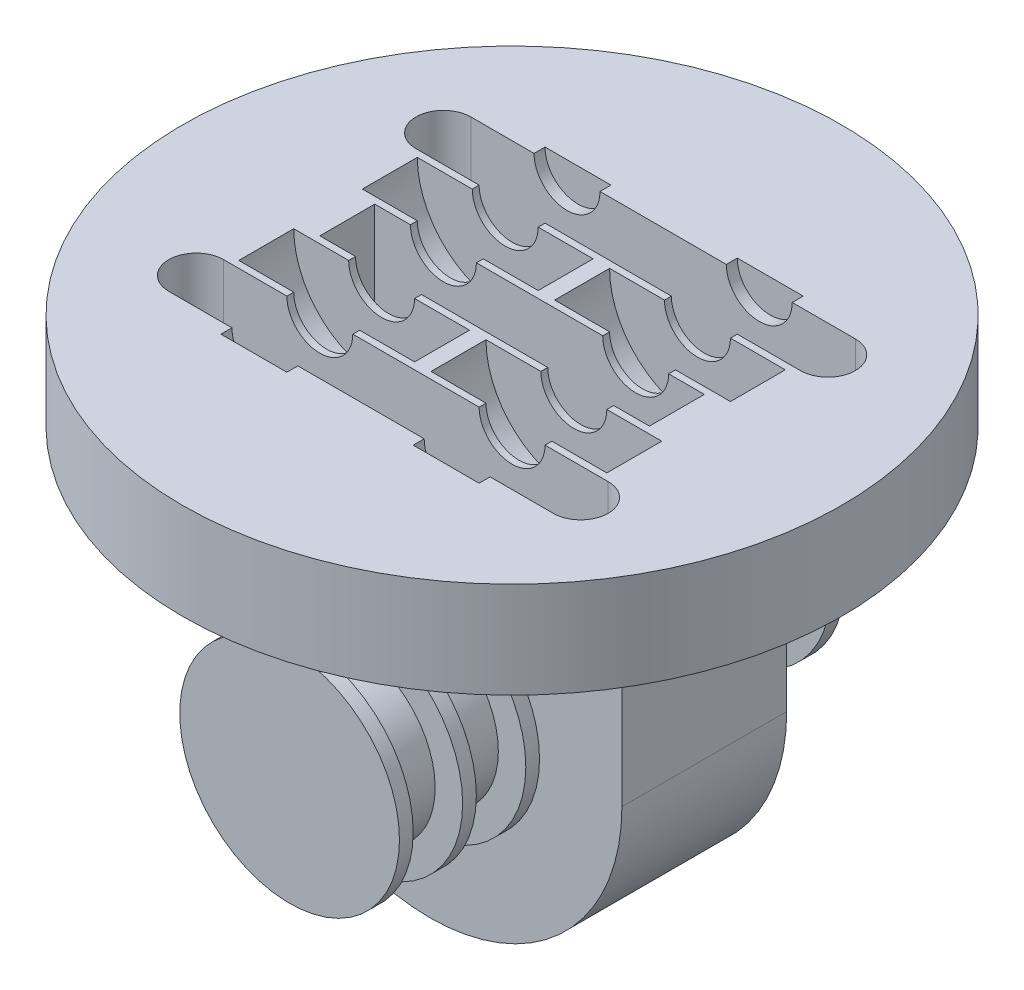
SolidWorks part; units mm, degrees
ref_plane "Front Plane" through (0, 0, 0) normal (0, 0, 1) x (1, 0, 0)
ref_plane "Top Plane" through (0, 0, 0) normal (0, 1, 0) x (1, 0, 0)
ref_plane "Right Plane" through (0, 0, 0) normal (1, 0, 0) x (0, 0, -1)
sketch "Sketch2" plane through (0, 0, 0) normal (0, 1, 0) x (1, 0, 0)
  circle A0 centre (0, 0) radius 60
  dimension "D1" = 120
extrude "Boss-Extrude1" add sketch "Sketch2" along normal blind 35
sketch "Sketch4" plane through (0, 0, 0) normal (0, 0, 1) x (1, 0, 0)
  line L0 (-35, 0) -> (-35, -35)
  line L1 (-60, 0) -> (60, 0) construction
  line L2 (0, 79.3854) -> (0, -134.1643) construction
  line L3 (35, 0) -> (35, -35)
  line L4 (-35, 0) -> (35, 0)
  arc A0 (-35, -35) -> (35, -35) centre (0, -35) ccw
  dimension "D1" = 35
  dimension "D2" = 35
extrude "Boss-Extrude2" add sketch "Sketch4" along normal mid plane 30
sketch "Sketch5" plane through (0, 0, 15) normal (0, 0, 1) x (1, 0, 0)
  line L0 (0, 0) -> (0, -35) construction
  line L1 (35, 0) -> (-35, 0) construction
  circle A0 centre (0, -35) radius 20
  dimension "D2" = 40
  dimension "D1" = 35
extrude "Boss-Extrude3" add sketch "Sketch5" along normal mid plane 5
sketch "Sketch6" plane through (0, 0, 17.5) normal (0, 0, 1) x (1, 0, 0)
  line L0 (0, 0) -> (0, -35) construction
  line L1 (35, 0) -> (-35, 0) construction
  circle A0 centre (0, -35) radius 15
  dimension "D2" = 30
  dimension "D1" = 35
extrude "Boss-Extrude4" add sketch "Sketch6" along normal blind 9
sketch "Sketch7" plane through (0, 0, 26.5) normal (0, 0, 1) x (1, 0, 0)
  line L0 (0, 0) -> (0, -35) construction
  line L1 (35, 0) -> (-35, 0) construction
  circle A0 centre (0, -35) radius 20
  dimension "D1" = 35
extrude "Boss-Extrude5" add sketch "Sketch7" along normal blind 2.5
sketch "Sketch8" plane through (0, 0, 29) normal (0, 0, 1) x (1, 0, 0)
  line L0 (0, 0) -> (0, -35) construction
  circle A0 centre (0, -35) radius 15
  dimension "D2" = 30
  dimension "D1" = 35
extrude "Boss-Extrude6" add sketch "Sketch8" along normal blind 9
sketch "Sketch9" plane through (0, 0, 38) normal (0, 0, 1) x (1, 0, 0)
  line L0 (0, 0) -> (0, -35) construction
  circle A0 centre (0, -35) radius 20
  dimension "D1" = 35
extrude "Boss-Extrude7" add sketch "Sketch9" along normal blind 2.5
mirror "Mirror1" about plane through (0, 0, 0) normal (0, 0, 1) of "Boss-Extrude3", "Boss-Extrude5", "Boss-Extrude4", "Boss-Extrude6", "Boss-Extrude7"
sketch "Sketch10" plane through (0, 35, 0) normal (0, 1, 0) x (1, 0, 0)
  line L0 (-56.8774, 0) -> (61.3412, 0) construction
  line L1 (-35, -22.5) -> (35, -22.5) construction
  line L2 (-35, -17.5) -> (35, -17.5)
  line L3 (-35, -27.5) -> (35, -27.5)
  arc A0 (-35, -17.5) -> (-35, -27.5) centre (-35, -22.5) ccw
  arc A1 (35, -27.5) -> (35, -17.5) centre (35, -22.5) ccw
  point P5 (0, -22.5)
  dimension "D1" = 17.5
  dimension "D2" = 70
  dimension "D3" = 10
extrude "Cut-Extrude1" cut sketch "Sketch10" against normal up to next
mirror "Mirror2" about plane through (0, 0, 0) normal (0, 0, 1) of "Cut-Extrude1"
sketch "Sketch11" plane through (0, 35, 0) normal (0, 1, 0) x (1, 0, 0)
  line L0 (-72.1407, 0) -> (83.8041, 0) construction
  line L1 (-30, 5) -> (30, 5)
  line L2 (-30, 5) -> (-30, -5)
  line L3 (-30, -5) -> (30, -5)
  line L4 (30, 5) -> (30, -5)
  line L5 (-30, 5) -> (30, -5) construction
  line L6 (-30, -5) -> (30, 5) construction
  point P0 (0, 0)
  dimension "D1" = 10
  dimension "D2" = 60
extrude "Cut-Extrude2" cut sketch "Sketch11" against normal up to surface (35 mm away) up to face at (0, 0, -22.5)
sketch "Sketch12" plane through (0, 0, -5) normal (0, 0, 1) x (1, 0, 0)
  line L1 (0, -3.4913) -> (0, 19.3044) construction
  line L7 (-30, 17.5) -> (30, 17.5) construction
  line L8 (-30, 35) -> (30, 35)
  line L9 (-30, 35) -> (-30, 0)
  line L10 (-30, 0) -> (30, 0)
  line L11 (30, 35) -> (30, 0)
  circle A0 centre (-17.5, 17.5) radius 6
  circle A1 centre (17.5, 17.5) radius 6
  point P9 (25, 35)
  dimension "D2" = 12
  dimension "D1" = 35
extrude "Cut-Extrude3" cut sketch "Sketch12" against normal offset from surface 2 and the other way offset from surface (34.5 mm away) 2 contours A1 | A0 up to face at (0, 17.5, -27.5) offset beyond the face yes other way up to face at (0, 17.5, 27.5)
sketch "Sketch15" plane through (0, 35, 0) normal (0, 1, 0) x (1, 0, 0)
  circle A0 centre (0, 0) radius 60
extrude "Cut-Extrude4" cut sketch "Sketch15" against normal blind 17.5
sketch "Sketch16" plane through (0, 17.5, 0) normal (0, 1, 0) x (1, 0, 0)
  circle A0 centre (0, 40) radius 4
  circle A1 centre (40, 0) radius 4
  circle A2 centre (0, -40) radius 4
  circle A3 centre (-40, 0) radius 4
  point P0 (0, 40)
  point P5 (40, 0)
  point P7 (0, -40)
  point P9 (-40, 0)
  point P11 (0, 0)
  point P24 (0, 0)
  point P25 (0, 0)
  dimension "D3" = 8
  dimension "D2" = 40
  dimension "D1" = 4
ref_plane "Plane1" through (0, 0, -11.25) normal (0, 0, 1) x (1, 0, 0)
sketch "Sketch17" plane through (0, 0, -11.25) normal (0, 0, 1) x (1, 0, 0)
  line L0 (-11.5, 17.5) -> (-23.5, 17.5) construction
  line L1 (0, 0) -> (0, 21.8545) construction
  line L2 (60, 17.5) -> (-60, 17.5) construction
  circle A0 centre (-17.5, 17.5) radius 16
  circle A1 centre (17.5, 17.5) radius 16
  dimension "D1" = 32
extrude "Cut-Extrude6" cut sketch "Sketch17" against normal mid plane 10
mirror "Mirror3" about plane through (0, 0, 0) normal (0, 0, 1) of "Cut-Extrude6"
equation "\"beltwidth\"= 9"
equation "\"D1@Boss-Extrude6\"=\"beltwidth\""
equation "\"D1@Boss-Extrude4\"=\"beltwidth\""
